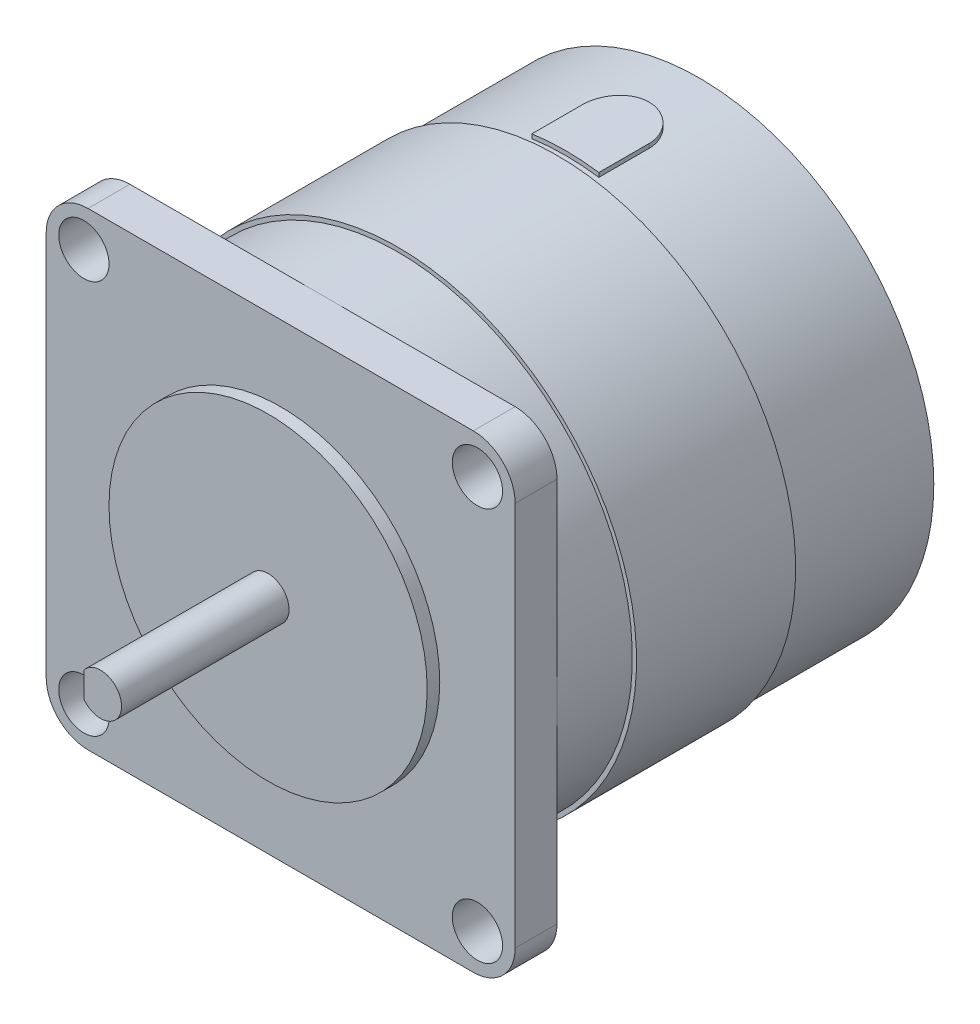
SolidWorks part; units mm, degrees
ref_plane "Front Plane" through (0, 0, 0) normal (0, 0, 1) x (1, 0, 0)
ref_plane "Top Plane" through (0, 0, 0) normal (0, 1, 0) x (1, 0, 0)
ref_plane "Right Plane" through (0, 0, 0) normal (1, 0, 0) x (0, 0, -1)
sketch "Sketch1" plane through (0, 0, 0) normal (0, 0, 1) x (1, 0, 0)
  circle A0 centre (0, 0) radius 28
  dimension "D1" = 56
extrude "Extrude1" add sketch "Sketch1" along normal blind 45
sketch "Sketch2" plane through (0, 0, 45) normal (0, 0, 1) x (1, 0, 0)
  line L1 (-28, 28) -> (28, 28)
  line L2 (-28, 28) -> (-28, -28)
  line L3 (-28, -28) -> (28, -28)
  line L4 (28, 28) -> (28, -28)
  line L5 (-28, 28) -> (28, -28) construction
  line L6 (-28, -28) -> (28, 28) construction
  point P0 (0, 0)
  dimension "D1" = 56
  dimension "D2" = 56
extrude "Extrude2" add sketch "Sketch2" along normal blind 5
sketch "Sketch4" plane through (0, 0, 50) normal (0, 0, 1) x (1, 0, 0)
  line L0 (-23.5, 23.5) -> (23.5, -23.5) construction
  line L1 (-23.5, 23.5) -> (23.5, 23.5) construction
  line L2 (-23.5, 23.5) -> (-23.5, -23.5) construction
  line L3 (-23.5, -23.5) -> (23.5, -23.5) construction
  line L4 (23.5, 23.5) -> (23.5, -23.5) construction
  circle A0 centre (-23.5, 23.5) radius 3
  circle A1 centre (23.5, 23.5) radius 3
  circle A2 centre (-23.5, -23.5) radius 3
  circle A3 centre (23.5, -23.5) radius 3
  dimension "D1" = 47
  dimension "D2" = 6
extrude "Extrude3" cut sketch "Sketch4" against normal blind 5
sketch "Sketch5" plane through (0, 0, 0) normal (0, 1, 0) x (1, 0, 0)
  line L0 (0, 0) -> (0, -55.8755) construction
  line L1 (28.5, -36) -> (28, -36)
  line L2 (28.5, -36) -> (28.5, -17)
  line L3 (28.5, -17) -> (28, -17)
  line L4 (28, -36) -> (28, -17)
  line L5 (28, -45) -> (0, -45) construction
  line L6 (28, -45) -> (28, 0) construction
  dimension "D1" = 9
  dimension "D2" = 0.5
  dimension "D3" = 19
revolve "Revolve2" add sketch "Sketch5" angle 360 about L0
sketch "Sketch7" plane through (0, 0, 50) normal (0, 0, 1) x (1, 0, 0)
  line L0 (0, -31.8868) -> (0, 35.9962) construction
  line L1 (-31.8617, 0) -> (32.3401, 0) construction
  circle A0 centre (0, 0) radius 19
extrude "Extrude4" add sketch "Sketch7" along normal blind 1.5
sketch "Sketch9" plane through (0, 0, 51.5) normal (0, 0, 1) x (1, 0, 0)
  circle A0 centre (0, 0) radius 2.5
  dimension "D1" = 5
extrude "Extrude5" add sketch "Sketch9" along normal blind 20
sketch "Sketch10" plane through (0, 0, 71.5) normal (0, 0, 1) x (1, 0, 0)
  line L1 (-2, 1.5) -> (-7, 1.5)
  line L2 (-2, 1.5) -> (-2, -1.5)
  line L3 (-2, -1.5) -> (-7, -1.5)
  line L4 (-7, 1.5) -> (-7, -1.5)
  circle A0 centre (0, 0) radius 2.5 construction
  dimension "D1" = 3
  dimension "D2" = 5
extrude "Extrude6" cut sketch "Sketch10" against normal blind 10
fillet "Fillet1" radius 5 4 edges at (-28, -28, 47.5) (28, -28, 47.5) (28, 28, 47.5) (-28, 28, 47.5)
sketch "Sketch11" plane through (0, 0, 0) normal (0, 1, 0) x (1, 0, 0)
  line L1 (-4, -16) -> (4, -16)
  line L2 (-4, -16) -> (-4, -10)
  line L3 (-4, -10) -> (4, -10) construction
  line L4 (4, -16) -> (4, -10)
  line L5 (0, -10) -> (0, 0) construction
  line L6 (28, 0) -> (-28, 0) construction
  arc A0 (-4, -10) -> (4, -10) centre (0, -10) cw
  dimension "D1" = 8
  dimension "D2" = 6
  dimension "D3" = 10
extrude "Extrude7" add sketch "Sketch11" along normal offset from surface (28.2179 mm away) 0.5
